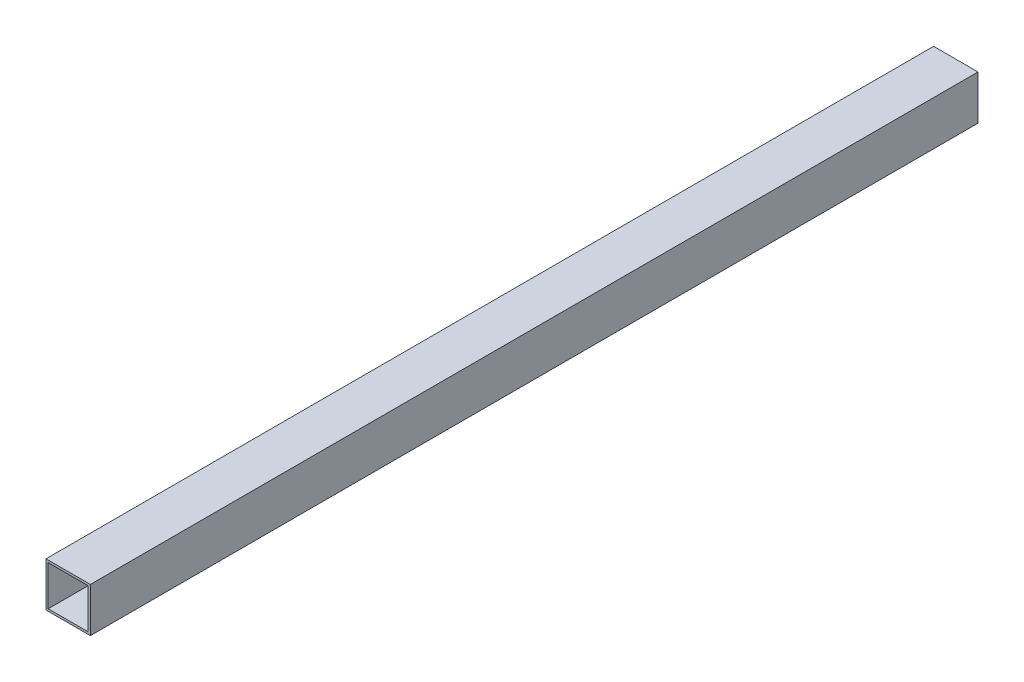
SolidWorks part; units mm, degrees
material "Aleación 1060"
ref_plane "Alzado" through (0, 0, 0) normal (0, 0, 1) x (1, 0, 0)
ref_plane "Planta" through (0, 0, 0) normal (0, 1, 0) x (1, 0, 0)
ref_plane "Vista lateral" through (0, 0, 0) normal (1, 0, 0) x (0, 0, -1)
sketch "Croquis1" plane through (0, 0, 0) normal (0, 0, 1) x (1, 0, 0)
  line L1 (20, -20) -> (-20, -20)
  line L2 (20, -20) -> (20, 20)
  line L3 (20, 20) -> (-20, 20)
  line L4 (-20, -20) -> (-20, 20)
  line L5 (20, -20) -> (-20, 20) construction
  line L6 (20, 20) -> (-20, -20) construction
  point P0 (0, 0)
  dimension "D1" = 40
  dimension "D2" = 40
extrude "Extruir-Lámina1" add sketch "Croquis1" along normal blind 800 thin
